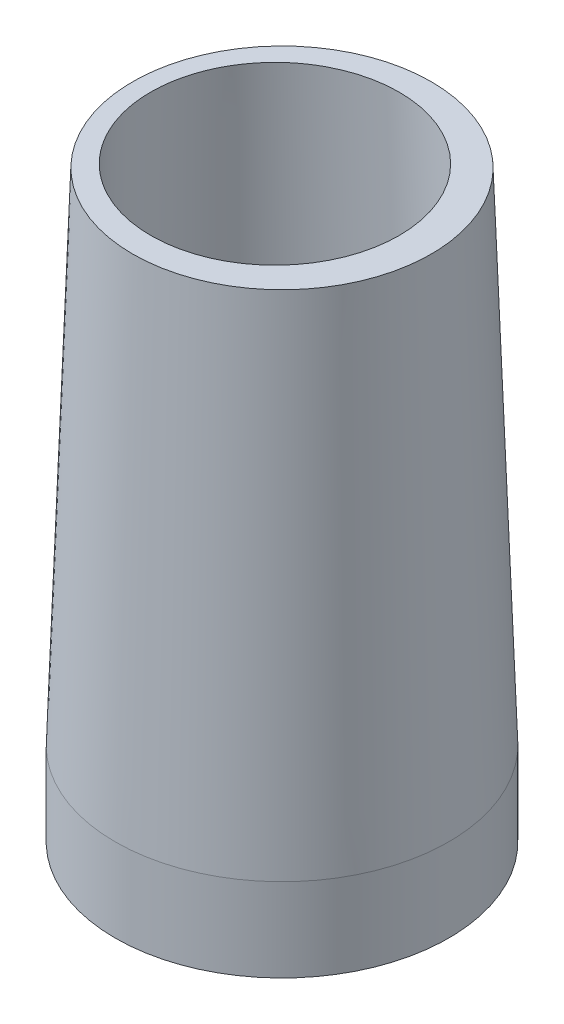
SolidWorks part; units mm, degrees
material "3.0205 (EN-AW 1200)"
ref_plane "Спереди" through (0, 0, 0) normal (0, 0, 1) x (1, 0, 0)
ref_plane "Сверху" through (0, 0, 0) normal (0, 1, 0) x (1, 0, 0)
ref_plane "Справа" through (0, 0, 0) normal (1, 0, 0) x (0, 0, -1)
sketch "Эскиз1" plane through (0, 0, 0) normal (0, 1, 0) x (1, 0, 0)
  circle A0 centre (0, 0) radius 20
  dimension "D1" = 40
extrude "Бобышка-Вытянуть1" add sketch "Эскиз1" along normal blind 60 draft 2 and the other way blind 10 contours A0
sketch "Эскиз3" plane through (0, 0, 0) normal (0, 0, 1) x (1, 0, 0)
  line L0 (-15.7439, 60) -> (-17.0017, 0)
  line L1 (17.9048, 60) -> (-17.9048, 60) construction
  line L2 (20, 0) -> (-20, 0) construction
  line L3 (-17.0017, 0) -> (-17.0017, -7.0303)
  line L4 (-17.0017, -7.0303) -> (-9.9011, -7.0303)
  line L5 (-9.9011, -7.0303) -> (0.0311, -2.1861)
  line L6 (0, 0) -> (-0.9005, 63.3838) construction
  line L7 (-0.9005, 63.3838) -> (0.2125, -14.9598) construction
  line L8 (0.0311, -2.1861) -> (-0.8524, 60)
  line L9 (-0.8524, 60) -> (-15.7439, 60)
  dimension "D1" = 29.78
  dimension "D2" = 34
  dimension "D3" = 20
revolve "Вырез-Повернуть1" cut sketch "Эскиз3" angle 360 about L8
